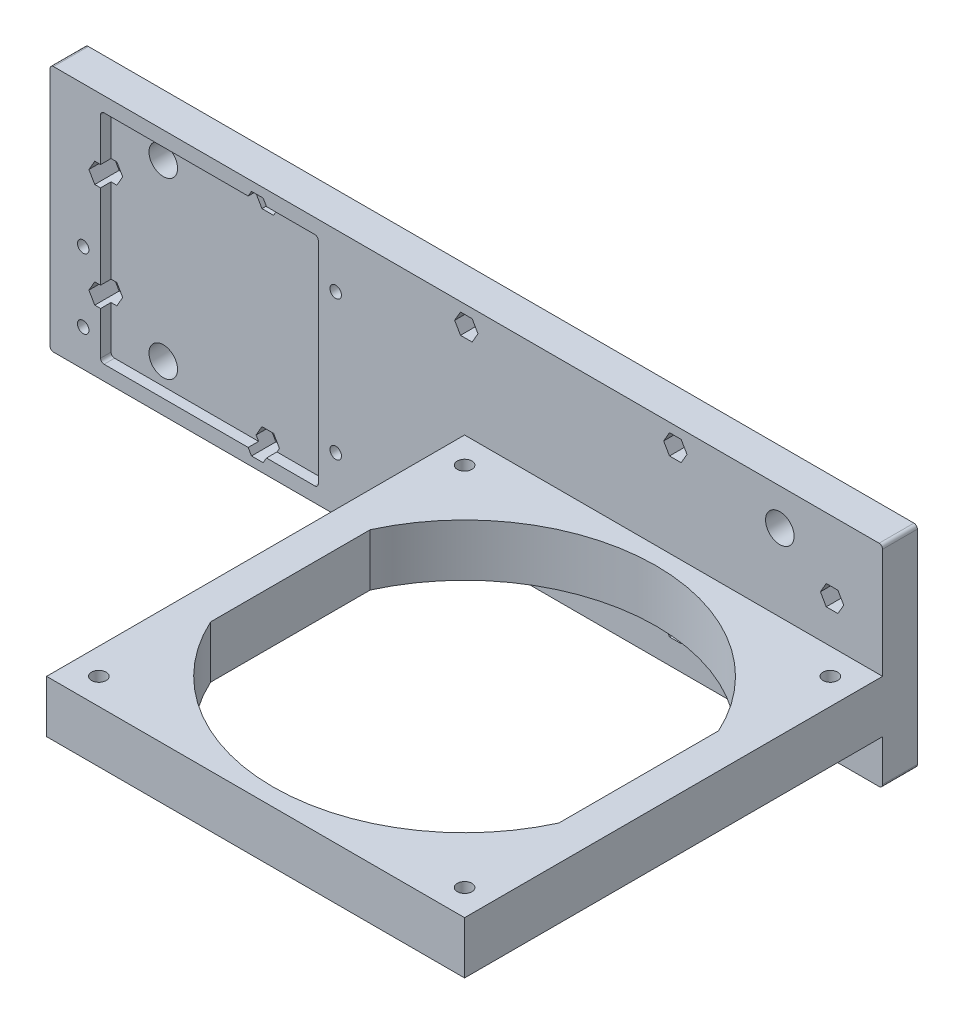
SolidWorks part; units mm, degrees
ref_plane "Front Plane" through (0, 0, 0) normal (0, 0, 1) x (1, 0, 0)
ref_plane "Top Plane" through (0, 0, 0) normal (0, 1, 0) x (1, 0, 0)
ref_plane "Right Plane" through (0, 0, 0) normal (1, 0, 0) x (0, 0, -1)
sketch "Sketch1" plane through (0, 0, 0) normal (0, 0, 1) x (1, 0, 0)
  line L13 (118.5, -25) -> (95.001, -25)
  line L26 (-118.5, -35.5) -> (-16, -35.5)
  line L27 (-119.5, -34.5) -> (-119.5, 34.5)
  line L28 (-118.5, 35.5) -> (118.5, 35.5)
  line L29 (119.5, -24) -> (119.5, 34.5)
  line L31 (84.999, -25) -> (-14, -25)
  line L32 (-15, -26) -> (-15, -34.5)
  circle A0 centre (-90, 25) radius 4.1
  circle A1 centre (90, 25) radius 4.1
  arc A2 (94.0204, -24.1961) -> (85.9796, -24.1961) centre (90, -25) ccw
  circle A3 centre (-90, -25) radius 4.1
  circle A8 centre (105, -15) radius 1.65
  circle A53 centre (-60, 30) radius 1.65
  circle A59 centre (-60, -30) radius 1.65
  circle A67 centre (-105, 15) radius 1.65
  circle A77 centre (-105, -15) radius 1.65
  circle A93 centre (-37.5, 20) radius 1.65
  circle A94 centre (-37.5, -20) radius 1.65
  circle A95 centre (-110, -5.0017) radius 1.65
  circle A96 centre (-110, -25) radius 1.65
  arc A97 (119.5, 34.5) -> (118.5, 35.5) centre (118.5, 34.5) ccw
  arc A99 (-119.5, -34.5) -> (-118.5, -35.5) centre (-118.5, -34.5) ccw
  arc A100 (-119.5, 34.5) -> (-118.5, 35.5) centre (-118.5, 34.5) cw
  arc A190 (118.5, -25) -> (119.5, -24) centre (118.5, -24) ccw
  arc A191 (94.0204, -24.1961) -> (95.001, -25) centre (95.001, -24) ccw
  arc A192 (85.9796, -24.1961) -> (84.999, -25) centre (84.999, -24) cw
  arc A193 (-15, -34.5) -> (-16, -35.5) centre (-16, -34.5) cw
  arc A194 (-14, -25) -> (-15, -26) centre (-14, -26) ccw
  circle A195 centre (60, 30) radius 1.65
  circle A196 centre (60, -15) radius 1.65
  circle A197 centre (105, 15) radius 1.65
  circle A198 centre (0, 30) radius 1.65
  circle A199 centre (0, -15) radius 1.65
  point P35 (85.9, -25)
extrude "Boss-Extrude1" add sketch "Sketch1" along normal blind 10
sketch "Sketch2" plane through (0, 0, 10) normal (0, 0, 1) x (1, 0, 0)
  line L1 (-101.6514, 15) -> (-103.3257, 17.9)
  line L2 (-103.3257, 17.9) -> (-106.6743, 17.9)
  line L3 (-106.6743, 17.9) -> (-108.3486, 15)
  line L4 (-108.3486, 15) -> (-106.6743, 12.1)
  line L5 (-106.6743, 12.1) -> (-103.3257, 12.1)
  line L6 (-103.3257, 12.1) -> (-101.6514, 15)
  line L7 (-101.6514, -15) -> (-103.3257, -12.1)
  line L8 (-103.3257, -12.1) -> (-106.6743, -12.1)
  line L9 (-106.6743, -12.1) -> (-108.3486, -15)
  line L10 (-108.3486, -15) -> (-106.6743, -17.9)
  line L11 (-106.6743, -17.9) -> (-103.3257, -17.9)
  line L12 (-103.3257, -17.9) -> (-101.6514, -15)
  line L13 (-56.6514, 30) -> (-58.3257, 32.9)
  line L14 (-58.3257, 32.9) -> (-61.6743, 32.9)
  line L15 (-61.6743, 32.9) -> (-63.3486, 30)
  line L16 (-63.3486, 30) -> (-61.6743, 27.1)
  line L17 (-61.6743, 27.1) -> (-58.3257, 27.1)
  line L18 (-58.3257, 27.1) -> (-56.6514, 30)
  line L31 (108.3486, -15) -> (106.6743, -12.1)
  line L32 (106.6743, -12.1) -> (103.3257, -12.1)
  line L33 (103.3257, -12.1) -> (101.6514, -15)
  line L34 (101.6514, -15) -> (103.3257, -17.9)
  line L35 (103.3257, -17.9) -> (106.6743, -17.9)
  line L36 (106.6743, -17.9) -> (108.3486, -15)
  line L37 (63.3486, 30) -> (61.6743, 32.9)
  line L38 (61.6743, 32.9) -> (58.3257, 32.9)
  line L39 (58.3257, 32.9) -> (56.6514, 30)
  line L40 (56.6514, 30) -> (58.3257, 27.1)
  line L41 (58.3257, 27.1) -> (61.6743, 27.1)
  line L42 (61.6743, 27.1) -> (63.3486, 30)
  line L43 (-56.6514, -30) -> (-58.3257, -27.1)
  line L44 (-58.3257, -27.1) -> (-61.6743, -27.1)
  line L45 (-61.6743, -27.1) -> (-63.3486, -30)
  line L46 (-63.3486, -30) -> (-61.6743, -32.9)
  line L47 (-61.6743, -32.9) -> (-58.3257, -32.9)
  line L48 (-58.3257, -32.9) -> (-56.6514, -30)
  line L60 (63.3486, -15) -> (61.6743, -12.1)
  line L61 (61.6743, -12.1) -> (58.3257, -12.1)
  line L62 (58.3257, -12.1) -> (56.6514, -15)
  line L63 (56.6514, -15) -> (58.3257, -17.9)
  line L64 (58.3257, -17.9) -> (61.6743, -17.9)
  line L65 (61.6743, -17.9) -> (63.3486, -15)
  line L66 (108.3486, 15) -> (106.6743, 17.9)
  line L67 (106.6743, 17.9) -> (103.3257, 17.9)
  line L68 (103.3257, 17.9) -> (101.6514, 15)
  line L69 (101.6514, 15) -> (103.3257, 12.1)
  line L70 (103.3257, 12.1) -> (106.6743, 12.1)
  line L71 (106.6743, 12.1) -> (108.3486, 15)
  line L72 (3.3486, 30) -> (1.6743, 32.9)
  line L73 (1.6743, 32.9) -> (-1.6743, 32.9)
  line L74 (-1.6743, 32.9) -> (-3.3486, 30)
  line L75 (-3.3486, 30) -> (-1.6743, 27.1)
  line L76 (-1.6743, 27.1) -> (1.6743, 27.1)
  line L77 (1.6743, 27.1) -> (3.3486, 30)
  line L78 (3.3486, -15) -> (1.6743, -12.1)
  line L79 (1.6743, -12.1) -> (-1.6743, -12.1)
  line L80 (-1.6743, -12.1) -> (-3.3486, -15)
  line L81 (-3.3486, -15) -> (-1.6743, -17.9)
  line L82 (-1.6743, -17.9) -> (1.6743, -17.9)
  line L83 (1.6743, -17.9) -> (3.3486, -15)
  circle A0 centre (105, 15) radius 2.9 construction
  circle A3 centre (60, -15) radius 2.9 construction
extrude "Cut-Extrude1" cut sketch "Sketch2" against normal offset from surface (7 mm away) 3 up to face at (18.75, -12.2154, 0)
sketch "Sketch3" plane through (0, 0, 10) normal (0, 0, 1) x (1, 0, 0)
  line L0 (-104, 31.25) -> (-43.5, 31.25)
  line L1 (-105, 30.25) -> (-105, -30.25)
  line L2 (-104, -31.25) -> (-43.5, -31.25)
  line L3 (-42.5, 30.25) -> (-42.5, -30.25)
  arc A0 (-43.5, 31.25) -> (-42.5, 30.25) centre (-43.5, 30.25) cw
  arc A1 (-43.5, -31.25) -> (-42.5, -30.25) centre (-43.5, -30.25) ccw
  arc A2 (-105, -30.25) -> (-104, -31.25) centre (-104, -30.25) ccw
  arc A3 (-104, 31.25) -> (-105, 30.25) centre (-104, 30.25) ccw
extrude "Cut-Extrude2" cut sketch "Sketch3" against normal blind 3
sketch "Sketch4" plane through (0, 0, 0) normal (0, 0, -1) x (-1, 0, 0)
  line L1 (40.8486, 20) -> (39.1743, 22.9)
  line L2 (39.1743, 22.9) -> (35.8257, 22.9)
  line L3 (35.8257, 22.9) -> (34.1514, 20)
  line L4 (34.1514, 20) -> (35.8257, 17.1)
  line L5 (35.8257, 17.1) -> (39.1743, 17.1)
  line L6 (39.1743, 17.1) -> (40.8486, 20)
  line L7 (40.8486, -20) -> (39.1743, -17.1)
  line L8 (39.1743, -17.1) -> (35.8257, -17.1)
  line L9 (35.8257, -17.1) -> (34.1514, -20)
  line L10 (34.1514, -20) -> (35.8257, -22.9)
  line L11 (35.8257, -22.9) -> (39.1743, -22.9)
  line L12 (39.1743, -22.9) -> (40.8486, -20)
  line L13 (113.3486, -25) -> (111.6743, -22.1)
  line L14 (111.6743, -22.1) -> (108.3257, -22.1)
  line L15 (108.3257, -22.1) -> (106.6514, -25)
  line L16 (106.6514, -25) -> (108.3257, -27.9)
  line L17 (108.3257, -27.9) -> (111.6743, -27.9)
  line L18 (111.6743, -27.9) -> (113.3486, -25)
  line L19 (113.3486, -5.0017) -> (111.6743, -2.1017)
  line L20 (111.6743, -2.1017) -> (108.3257, -2.1017)
  line L21 (108.3257, -2.1017) -> (106.6514, -5.0017)
  line L22 (106.6514, -5.0017) -> (108.3257, -7.9017)
  line L23 (108.3257, -7.9017) -> (111.6743, -7.9017)
  line L24 (111.6743, -7.9017) -> (113.3486, -5.0017)
  circle A0 centre (37.5, 20) radius 2.9 construction
  circle A1 centre (37.5, -20) radius 2.9 construction
  circle A2 centre (110, -25) radius 2.9 construction
  circle A3 centre (110, -5.0017) radius 2.9 construction
extrude "Cut-Extrude3" cut sketch "Sketch4" against normal blind 5
sketch "Sketch5" plane through (0, 0, 10) normal (0, 0, 1) x (1, 0, 0)
  line L7 (-0.5, 2.9) -> (119.5, 2.9)
  line L8 (-0.5, 2.9) -> (-0.5, -12.1)
  line L9 (-0.5, -12.1) -> (119.5, -12.1)
  line L10 (119.5, 2.9) -> (119.5, -12.1)
extrude "Boss-Extrude2" add sketch "Sketch5" along normal blind 120
sketch "Sketch6" plane through (0, -12.1, 0) normal (0, -1, 0) x (1, 0, 0)
  line L3 (9.5, 92.9129) -> (9.5, 47.0871)
  line L5 (109.5, 92.9129) -> (109.5, 47.0871)
  arc A0 (9.5, 47.0871) -> (109.5, 47.0871) centre (59.5, 70) ccw
  arc A1 (109.5, 92.9129) -> (9.5, 92.9129) centre (59.5, 70) ccw
  circle A2 centre (7, 122.5) radius 2.1
  circle A3 centre (7, 17.5) radius 2.1
  circle A4 centre (112, 17.5) radius 2.1
  circle A5 centre (112, 122.5) radius 2.1
extrude "Cut-Extrude4" cut sketch "Sketch6" against normal up to surface (15 mm away) up to face at (59.5, 2.9, 70)
